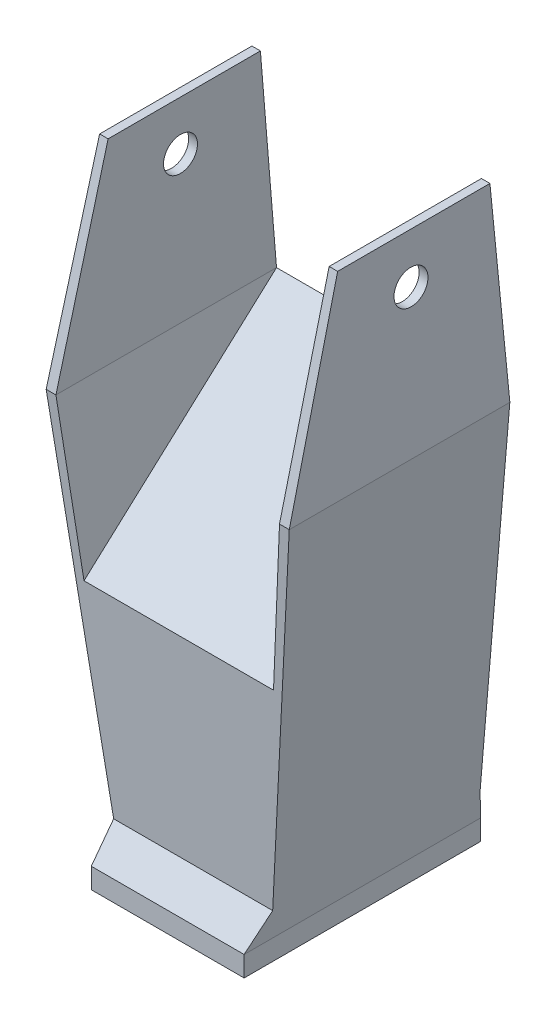
SolidWorks part; units mm, degrees
ref_plane "Front Plane" through (0, 0, 0) normal (0, 0, 1) x (1, 0, 0)
ref_plane "Top Plane" through (0, 0, 0) normal (0, 1, 0) x (1, 0, 0)
ref_plane "Right Plane" through (0, 0, 0) normal (1, 0, 0) x (0, 0, -1)
sketch "Sketch2" plane through (0, 0, 0) normal (1, 0, 0) x (0, 0, -1)
  line L0 (-35.2512, -109.956) -> (34.3588, -109.956)
  line L1 (34.3588, -109.956) -> (33.3163, -102.064)
  line L2 (33.3163, -102.064) -> (29.6988, 5.0049)
  line L3 (29.6988, 5.0049) -> (24.5837, 63.0049)
  line L4 (24.5837, 63.0049) -> (-20.2563, 63.0049)
  line L5 (-20.2563, 63.0049) -> (-35.2512, 5.0049)
  line L6 (-35.2512, 5.0049) -> (-27.7537, -102.064)
  line L7 (-27.7537, -102.064) -> (-35.2512, -109.956)
  dimension "D1" = 69.61
  dimension "D2" = 44.84
  dimension "D3" = 64.95
  dimension "D4" = 61.07
  dimension "D5" = 58
extrude "Boss-Extrude1" add sketch "Sketch2" along normal blind 71.58
sketch "Sketch4" plane through (0, 0, 0) normal (0, 0, 1) x (1, 0, 0)
  line L1 (71.58, -109.956) -> (0, -109.956) construction
  line L2 (58.29, -109.956) -> (71.58, 5.0049)
  line L7 (0, 63.0049) -> (0, 5.0049) construction
  line L8 (71.58, 5.0049) -> (0, 5.0049) construction
  line L9 (0, 5.0049) -> (13.29, -109.956)
  line L16 (0, 5.0049) -> (0, -109.956)
  line L17 (0, -109.956) -> (13.29, -109.956)
  line L18 (58.29, -109.956) -> (71.58, -109.956)
  line L19 (71.58, -109.956) -> (71.58, 5.0049)
extrude "Cut-Extrude2" cut sketch "Sketch4" against normal through all and the other way through all
sketch "Sketch5" plane through (0, 0, 0) normal (0, 0, 1) x (1, 0, 0)
  line L1 (0, 5.0049) -> (0, 63.0049)
  line L2 (0, 63.0049) -> (0.75, 63.0049)
  line L3 (71.58, 63.0049) -> (0, 63.0049) construction
  line L4 (0.75, 63.0049) -> (0, 5.0049)
  line L5 (71.58, 63.0049) -> (70.83, 63.0049)
  line L6 (70.83, 63.0049) -> (71.58, 5.0049)
  line L7 (71.58, 5.0049) -> (71.58, 63.0049)
  dimension "D1" = 0.75
  dimension "D2" = 0.75
extrude "Cut-Extrude3" cut sketch "Sketch5" against normal through all and the other way through all
sketch "Sketch9" plane through (0, 0, 0) normal (0, 0, 1) x (1, 0, 0)
  line L0 (0.375, 34.0049) -> (71.205, 34.0049) construction
  line L1 (3.25, 63.0049) -> (68.33, 63.0049)
  line L2 (3.25, 63.0049) -> (2.875, 5.0049)
  line L3 (2.875, 5.0049) -> (68.705, 5.0049)
  line L4 (68.33, 63.0049) -> (68.705, 5.0049)
  line L5 (0.75, 63.0049) -> (0, 5.0049) construction
  line L6 (71.58, 5.0049) -> (70.83, 63.0049) construction
  line L7 (71.205, 34.0049) -> (35.79, 34.0049) construction
  line L8 (35.79, 34.0049) -> (35.79, 63.0049) construction
  line L9 (70.83, 63.0049) -> (0.75, 63.0049) construction
  line L10 (35.79, 34.0049) -> (35.79, 5.0049) construction
  dimension "D1" = 65.08
  dimension "D2" = 65.83
extrude "Cut-Extrude4" cut sketch "Sketch9" against normal through all and the other way through all
sketch "Sketch16" plane through (0, 0, 0) normal (1, 0, 0) x (0, 0, -1)
  line L0 (0.8837, 71.7124) -> (0.8837, 5.0049) construction
  line L1 (-35.2512, 5.0049) -> (29.6988, 5.0049) construction
  line L2 (25.6343, 48.4049) -> (-23.3359, 48.4049) construction
  circle A0 centre (1.1492, 48.4049) radius 5
  dimension "D1" = 14.6
  dimension "D2" = 23.7
extrude "Cut-Extrude11" cut sketch "Sketch16" along normal through all
sketch "Sketch17" plane through (0, -109.956, 0) normal (0, -1, 0) x (1, 0, 0)
  line L1 (13.29, 35.2512) -> (58.29, 35.2512)
  line L2 (13.29, 35.2512) -> (13.29, -34.3588)
  line L3 (13.29, -34.3588) -> (58.29, -34.3588)
  line L4 (58.29, 35.2512) -> (58.29, -34.3588)
extrude "Boss-Extrude2" add sketch "Sketch17" along normal blind 6
sketch "Sketch18" plane through (0, -115.956, 0) normal (0, -1, 0) x (1, 0, 0)
  line L0 (13.29, 35.2512) -> (58.29, -34.3588) construction
  circle A0 centre (35.79, 0.4462) radius 4.9
extrude "Boss-Extrude3" add sketch "Sketch18" along normal blind 10
sketch "Sketch19" plane through (0, 0, 0) normal (0, 0, 1) x (1, 0, 0)
  line L0 (2.875, 5.0049) -> (7.8923, -41.4951)
  line L1 (7.8923, -41.4951) -> (63.6877, -41.4951)
  line L2 (63.6877, -41.4951) -> (68.705, 5.0049)
  line L3 (2.875, 5.0049) -> (68.705, 5.0049) construction
  line L4 (68.705, 5.0049) -> (2.875, 5.0049)
  line L6 (0, 5.0049) -> (12.3776, -102.064) construction
  line L7 (59.2024, -102.064) -> (71.58, 5.0049) construction
  dimension "D1" = 104.5
  dimension "D2" = 2.5
  dimension "D3" = 2.5
extrude "Cut-Extrude12" cut sketch "Sketch19" against normal up to surface and the other way up to surface up to face at (35.79, -30.6847, -30.9047) other way up to face at (35.79, -30.6847, 32.752)
sketch "Sketch20" plane through (3.3757, 0.3642, 0) normal (0.9942, 0.1073, 0) x (0, 0, -1)
  line L0 (29.6988, 4.6676) -> (-31.995, -42.1023)
  line L1 (-31.995, -42.1023) -> (31.2699, -42.1023)
  line L2 (31.2699, -42.1023) -> (29.6988, 4.6676)
extrude "Boss-Extrude4" add sketch "Sketch20" along direction (1, 0, 0) on the side of the normal up to surface (55.7955 mm away)
